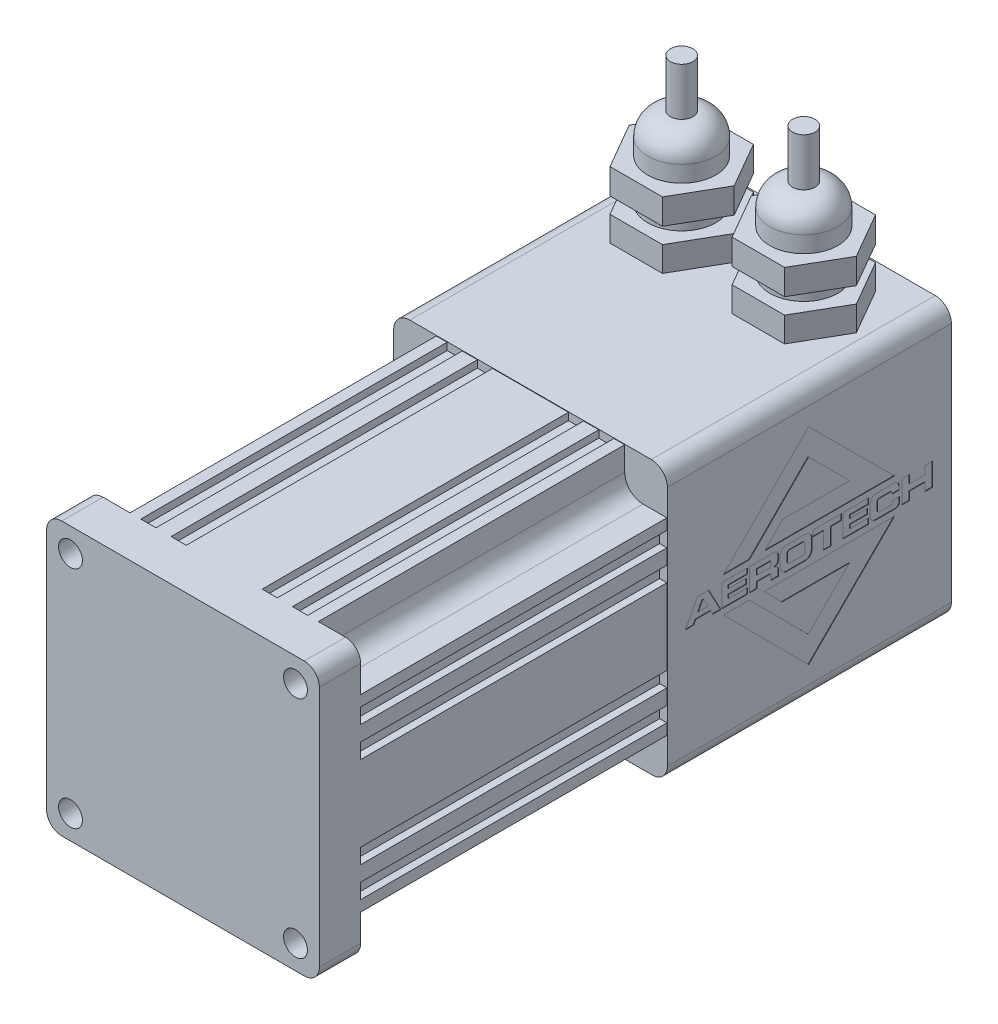
SolidWorks part; units mm, degrees
ref_plane "Front" through (0, 0, 0) normal (0, 0, 1) x (1, 0, 0)
ref_plane "Top" through (0, 0, 0) normal (0, 1, 0) x (1, 0, 0)
ref_plane "Right" through (0, 0, 0) normal (1, 0, 0) x (0, 0, -1)
sketch "Sketch1" plane through (0, 0, 0) normal (0, 0, 1) x (1, 0, 0)
  line L0 (-25.4, 28.575) -> (25.4, 28.575)
  line L1 (-28.575, -25.4) -> (-28.575, 25.4)
  line L2 (25.4, -28.575) -> (-25.4, -28.575)
  line L3 (28.575, 25.4) -> (28.575, -25.4)
  line L4 (-23.5712, -23.5712) -> (-23.5712, 23.5712) construction
  line L5 (-23.5712, 23.5712) -> (23.5712, 23.5712) construction
  line L6 (23.5712, 23.5712) -> (23.5712, -23.5712) construction
  line L7 (23.5712, -23.5712) -> (-23.5712, -23.5712) construction
  line L8 (0, -49.1414) -> (0, 49.1414) construction
  line L9 (31.5425, 0) -> (-31.5425, 0) construction
  arc A0 (28.575, 25.4) -> (25.4, 28.575) centre (25.4, 25.4) ccw
  arc A1 (-25.4, 28.575) -> (-28.575, 25.4) centre (-25.4, 25.4) ccw
  arc A2 (-28.575, -25.4) -> (-25.4, -28.575) centre (-25.4, -25.4) ccw
  arc A3 (25.4, -28.575) -> (28.575, -25.4) centre (25.4, -25.4) ccw
  circle A4 centre (-23.5712, -23.5712) radius 2.5
  circle A5 centre (23.5712, -23.5712) radius 2.5
  circle A6 centre (23.5712, 23.5712) radius 2.5
  circle A7 centre (-23.5712, 23.5712) radius 2.5
  point P20 (0, 28.575)
  point P23 (28.575, 0)
  point P26 (23.5712, 0)
  point P27 (-23.5712, 0)
  point P28 (0, 23.5712)
  dimension "D1" = 3.175
  dimension "D2" = 57.15
  dimension "D4" = 5
  dimension "D5" = 47.1424
  dimension "D3" = 57.15
  dimension "D6" = 47.1424
extrude "Front Mount Plate" add sketch "Sketch1" along normal blind 8.64
sketch "Sketch2" plane through (0, 0, 0) normal (0, 0, -1) x (-1, 0, 0)
  line L0 (-28.575, -25.4) -> (-28.575, 25.4) construction
  line L1 (25.4, -28.575) -> (-25.4, -28.575) construction
  line L2 (28.575, 25.4) -> (28.575, -25.4) construction
  line L3 (-25.4, 28.575) -> (25.4, 28.575) construction
  line L4 (-28.575, -25.4) -> (-28.575, 25.4)
  line L5 (25.4, -28.575) -> (-25.4, -28.575)
  line L6 (28.575, 25.4) -> (28.575, -25.4)
  line L7 (-25.4, 28.575) -> (25.4, 28.575)
  arc A0 (-28.575, -25.4) -> (-25.4, -28.575) centre (-25.4, -25.4) ccw construction
  arc A1 (25.4, -28.575) -> (28.575, -25.4) centre (25.4, -25.4) ccw construction
  arc A2 (28.575, 25.4) -> (25.4, 28.575) centre (25.4, 25.4) ccw construction
  arc A3 (-25.4, 28.575) -> (-28.575, 25.4) centre (-25.4, 25.4) ccw construction
  arc A4 (-28.575, -25.4) -> (-25.4, -28.575) centre (-25.4, -25.4) ccw
  arc A5 (25.4, -28.575) -> (28.575, -25.4) centre (25.4, -25.4) ccw
  arc A6 (28.575, 25.4) -> (25.4, 28.575) centre (25.4, 25.4) ccw
  arc A7 (-25.4, 28.575) -> (-28.575, 25.4) centre (-25.4, 25.4) ccw
extrude "Motor" add sketch "Sketch2" along normal blind 64.18
sketch "Sketch3" plane through (0, 0, 0) normal (0, 0, 1) x (1, 0, 0)
  line L0 (-28.575, 19.7358) -> (-23.5712, 19.7358)
  line L1 (-19.7358, 28.575) -> (-17.4752, 28.575)
  line L2 (-17.4752, 28.575) -> (-17.4752, 27.051)
  line L3 (-17.4752, 27.051) -> (-14.3002, 27.051)
  line L4 (-14.3002, 27.051) -> (-14.3002, 28.575)
  line L5 (-14.3002, 28.575) -> (-11.1252, 28.575)
  line L6 (-11.1252, 28.575) -> (-11.1252, 27.051)
  line L7 (-11.1252, 27.051) -> (-7.9502, 27.051)
  line L8 (-7.9502, 27.051) -> (-7.9502, 28.575)
  line L9 (-7.9502, 28.575) -> (7.9502, 28.575)
  line L10 (7.9502, 28.575) -> (7.9502, 27.051)
  line L11 (7.9502, 27.051) -> (11.1252, 27.051)
  line L12 (11.1252, 27.051) -> (11.1252, 28.575)
  line L13 (11.1252, 28.575) -> (14.3002, 28.575)
  line L14 (14.3002, 28.575) -> (14.3002, 27.051)
  line L15 (14.3002, 27.051) -> (17.4752, 27.051)
  line L16 (17.4752, 27.051) -> (17.4752, 28.575)
  line L17 (17.4752, 28.575) -> (19.7358, 28.575)
  line L18 (-19.7358, 28.575) -> (-19.7358, 23.5712)
  line L19 (-25.4, 28.575) -> (25.4, 28.575) construction
  line L20 (-28.575, -25.4) -> (-28.575, 25.4) construction
  line L21 (17.4752, 28.575) -> (14.3002, 28.575)
  line L22 (11.1252, 28.575) -> (7.9502, 28.575)
  line L23 (7.9502, 28.575) -> (8.0896, 28.5819)
  line L24 (-7.9502, 28.575) -> (-11.1252, 28.575)
  line L25 (-14.3002, 28.575) -> (-17.4752, 28.575)
  line L26 (-25.4, 28.575) -> (-19.7358, 28.575)
  line L27 (-28.575, 25.4) -> (-28.575, 19.7358)
  arc A0 (-23.5712, 19.7358) -> (-19.7358, 23.5712) centre (-23.5712, 23.5712) ccw
  arc A1 (-25.4, 28.575) -> (-28.575, 25.4) centre (-25.4, 25.4) ccw construction
  arc A2 (-25.4, 28.575) -> (-28.575, 25.4) centre (-25.4, 25.4) ccw
  dimension "D3" = 3.8354
  dimension "D1" = 3.175
  dimension "D2" = 1.524
  dimension "D4" = 8.8392
  dimension "D5" = 8.8392
  dimension "D6" = 15.9004
  dimension "D7" = 2.2606
extrude "Motor Fins" cut sketch "Sketch3" against normal through all contours L16 L21 L14 L15 | L12 L22 L10 L11 | L8 L24 L6 L7 | L4 L25 L2 L3 | L26 A2 L27 L0 A0 L18
ref_axis "Axis1" through (0, 0, -130.3065) along (0, 0, 1)
pattern_circular "Motor Fins Pattern" count 4 over 270 about axis through (0, 0, 0) along (0, 0, 1) of "Motor Fins"
sketch "Sketch4" plane through (0, 0, -64.18) normal (0, 0, -1) x (-1, 0, 0)
  line L0 (-25.3, 28.675) -> (25.3, 28.675)
  line L1 (28.675, 25.3) -> (28.675, -25.3)
  line L2 (25.5, -28.475) -> (-25.5, -28.475)
  line L3 (-28.675, -25.3) -> (-28.675, 25.3)
  line L4 (0, 28.675) -> (0, 0) construction
  line L5 (0, 0) -> (28.675, 0) construction
  line L6 (7.9502, 28.575) -> (-7.9502, 28.575) construction
  line L7 (-28.575, 7.9502) -> (-28.575, -7.9502) construction
  line L8 (-7.9502, -28.575) -> (7.9502, -28.575) construction
  line L10 (28.575, -7.9502) -> (28.575, 7.9502) construction
  arc A4 (-28.675, -25.3) -> (-25.5, -28.475) centre (-25.5, -25.3) ccw
  arc A5 (25.5, -28.475) -> (28.675, -25.3) centre (25.5, -25.3) ccw
  arc A6 (28.675, 25.3) -> (25.3, 28.675) centre (25.3, 25.3) ccw
  arc A7 (-25.3, 28.675) -> (-28.675, 25.3) centre (-25.3, 25.3) ccw
  arc A8 (-28.575, -25.4) -> (-25.4, -28.575) centre (-25.4, -25.4) ccw construction
  arc A9 (25.4, -28.575) -> (28.575, -25.4) centre (25.4, -25.4) ccw construction
  dimension "D1" = 0.1
  dimension "D2" = 0.1
  dimension "D3" = 0.1
  dimension "D4" = 0.1
extrude "Enc Can" add sketch "Sketch4" along normal blind 59.51
sketch "Sketch11" plane through (28.675, 0, 0) normal (1, 0, 0) x (0, 0, -1)
  line L0 (88.9565, 2.3168) -> (93.1221, 2.3168)
  line L1 (94.4835, 0.9554) -> (94.4835, -1.0386)
  line L2 (93.0789, -2.4432) -> (89.2687, -2.4432)
  line L3 (87.8027, -0.9773) -> (87.8027, 0.9554)
  line L4 (91.0794, 1.1637) -> (92.5563, 1.1637)
  line L5 (92.998, 0.722) -> (92.998, -0.8097)
  line L6 (92.5621, -1.2456) -> (89.8225, -1.2456)
  line L7 (89.3492, -0.7722) -> (89.3492, 0.7301)
  line L8 (89.7934, 1.1715) -> (91.0794, 1.1637)
  line L9 (82.9208, 1.1044) -> (85.6816, 1.1044)
  line L10 (85.9333, 0.8526) -> (85.9333, 0.248)
  line L11 (85.6723, -0.0131) -> (82.9208, -0.0131)
  line L12 (82.9208, -0.0131) -> (82.9208, 1.1044)
  line L13 (81.4158, 2.3168) -> (86.5203, 2.3168)
  line L14 (87.4271, 1.41) -> (87.4271, 0.4495)
  line L15 (87.4271, -2.4432) -> (85.923, -2.4432)
  line L16 (85.923, -2.4432) -> (85.923, -1.6109)
  line L17 (85.5149, -1.2029) -> (82.9083, -1.2029)
  line L18 (82.9083, -1.2029) -> (82.9083, -2.4432)
  line L19 (82.9083, -2.4432) -> (81.4158, -2.4432)
  line L20 (81.4158, -2.4432) -> (81.4158, 2.3168)
  line L21 (111.2718, 0.54) -> (112.7627, 0.54)
  line L22 (112.7627, 0.54) -> (112.7627, 1.2972)
  line L23 (111.7431, 2.3168) -> (107.9351, 2.3168)
  line L24 (106.6708, 1.0525) -> (106.6708, -1.2129)
  line L25 (107.9011, -2.4432) -> (111.9771, -2.4432)
  line L26 (112.8433, -1.577) -> (112.8433, -0.6783)
  line L27 (112.8433, -0.6783) -> (111.3281, -0.6783)
  line L28 (111.3281, -0.6783) -> (111.3281, -0.9515)
  line L29 (110.9108, -1.3689) -> (108.715, -1.3689)
  line L30 (108.1674, -0.8212) -> (108.1674, 0.5695)
  line L31 (108.6971, 1.0992) -> (110.8691, 1.0992)
  line L32 (111.2718, 0.6965) -> (111.2718, 0.54)
  line L33 (67.9134, -2.4432) -> (70.519, 2.3168)
  line L34 (70.519, 2.3168) -> (72.8346, 2.3168)
  line L35 (72.8346, 2.3168) -> (75.3883, -2.4432)
  line L36 (75.3883, -2.4432) -> (73.679, -2.4432)
  line L37 (73.679, -2.4432) -> (73.2611, -1.6252)
  line L38 (73.2611, -1.6252) -> (70.1097, -1.6252)
  line L39 (70.1097, -1.6252) -> (69.6824, -2.4432)
  line L40 (69.6824, -2.4432) -> (67.9134, -2.4432)
  line L41 (70.6406, -0.5321) -> (72.7163, -0.5321)
  line L42 (72.7163, -0.5321) -> (71.8147, 1.1708)
  line L43 (71.8147, 1.1708) -> (71.5421, 1.1708)
  line L44 (71.5421, 1.1708) -> (70.6406, -0.5321)
  line L45 (75.5917, 2.3168) -> (80.9222, 2.3168)
  line L46 (80.9222, 2.3168) -> (80.9222, 1.178)
  line L47 (80.9222, 1.178) -> (77.0104, 1.178)
  line L48 (77.0104, 1.178) -> (77.0104, 0.5173)
  line L49 (77.0104, 0.5173) -> (80.7195, 0.5173)
  line L50 (80.7195, 0.5173) -> (80.7195, -0.5529)
  line L51 (80.7195, -0.5529) -> (77.0104, -0.5529)
  line L52 (77.0104, -0.5529) -> (77.0104, -1.2947)
  line L53 (77.0104, -1.2947) -> (80.9222, -1.2947)
  line L54 (80.9222, -1.2947) -> (80.9222, -2.4432)
  line L55 (80.9222, -2.4432) -> (75.5917, -2.4432)
  line L56 (75.5917, -2.4432) -> (75.5917, 2.3168)
  line L57 (94.7459, 2.3168) -> (100.6554, 2.3168)
  line L58 (100.6554, 2.3168) -> (100.6554, 1.0852)
  line L59 (100.6554, 1.0852) -> (98.455, 1.0852)
  line L60 (98.455, 1.0852) -> (98.455, -2.4432)
  line L61 (98.455, -2.4432) -> (96.8755, -2.4432)
  line L62 (96.8755, -2.4432) -> (96.8755, 1.0844)
  line L63 (96.8755, 1.0844) -> (94.7459, 1.0844)
  line L64 (94.7459, 1.0844) -> (94.7459, 2.3168)
  line L65 (100.9451, 2.3168) -> (106.3069, 2.3168)
  line L66 (106.3069, 2.3168) -> (106.3069, 1.177)
  line L67 (106.3069, 1.177) -> (102.4198, 1.177)
  line L68 (102.4198, 1.177) -> (102.4198, 0.5302)
  line L69 (102.4198, 0.5302) -> (106.1167, 0.5302)
  line L70 (106.1167, 0.5302) -> (106.1167, -0.5415)
  line L71 (106.1167, -0.5415) -> (102.4198, -0.5415)
  line L72 (102.4198, -0.5415) -> (102.4198, -1.2892)
  line L73 (102.4198, -1.2892) -> (106.3069, -1.2892)
  line L74 (106.3069, -1.2892) -> (106.3069, -2.4432)
  line L75 (106.3069, -2.4432) -> (100.9451, -2.4432)
  line L76 (100.9451, -2.4432) -> (100.9451, 2.3168)
  line L77 (113.3445, 2.3168) -> (114.895, 2.3168)
  line L78 (114.895, 2.3168) -> (114.895, 0.6117)
  line L79 (114.895, 0.6117) -> (118.1704, 0.6117)
  line L80 (118.1704, 0.6117) -> (118.1704, 2.3168)
  line L81 (118.1704, 2.3168) -> (119.7597, 2.3168)
  line L82 (119.7597, 2.3168) -> (119.7597, -2.4432)
  line L83 (119.7597, -2.4432) -> (118.1704, -2.4432)
  line L84 (118.1704, -2.4432) -> (118.1704, -0.7247)
  line L85 (118.1704, -0.7247) -> (114.895, -0.7247)
  line L86 (114.895, -0.7247) -> (114.895, -2.4432)
  line L87 (114.895, -2.4432) -> (113.3445, -2.4432)
  line L88 (113.3445, -2.4432) -> (113.3445, 2.3168)
  line L89 (75.9285, -3.7308) -> (81.3786, -3.7308)
  line L90 (81.3786, -3.7308) -> (93.6773, -16.0962)
  line L91 (93.6773, -16.0962) -> (102.3262, -7.494)
  line L92 (102.3262, -7.494) -> (88.1992, -7.494)
  line L93 (88.1992, -7.494) -> (84.4729, -3.7308)
  line L94 (84.4729, -3.7308) -> (111.7772, -3.7308)
  line L95 (111.7772, -3.7308) -> (93.7559, -21.6549)
  line L96 (93.7559, -21.6549) -> (75.9285, -3.7308)
  line L97 (75.9285, 3.6038) -> (93.7559, 21.5279)
  line L98 (93.7559, 21.5279) -> (111.7772, 3.6038)
  line L99 (75.9285, 3.6038) -> (81.3786, 3.6038)
  line L100 (81.3786, 3.6038) -> (93.7413, 16.0335)
  line L101 (93.7413, 16.0335) -> (102.3901, 7.4313)
  line L102 (102.3901, 7.4313) -> (88.2631, 7.4313)
  line L103 (88.2631, 7.4313) -> (84.6029, 3.6038)
  line L104 (84.6029, 3.6038) -> (111.7772, 3.6038)
  line L105 (87.4271, -1.2037) -> (87.4271, -2.4432)
  line L106 (-23.1846, 0) -> (123.69, 0) construction
  line L107 (93.935, 25.3) -> (93.935, -74.4783) construction
  line L108 (123.69, 25.3) -> (64.18, 25.3) construction
  line L109 (123.69, 25.3) -> (123.69, -25.3) construction
  arc A0 (93.1221, 2.3168) -> (94.4835, 0.9554) centre (93.1221, 0.9554) cw
  arc A1 (94.4835, -1.0386) -> (93.0789, -2.4432) centre (93.0789, -1.0386) cw
  arc A2 (89.2687, -2.4432) -> (87.8027, -0.9773) centre (89.2687, -0.9773) cw
  arc A3 (87.8027, 0.9554) -> (88.9565, 2.3168) centre (89.1828, 0.9554) cw
  arc A4 (92.5563, 1.1637) -> (92.998, 0.722) centre (92.5563, 0.722) cw
  arc A5 (92.998, -0.8097) -> (92.5621, -1.2456) centre (92.5621, -0.8097) cw
  arc A6 (89.8225, -1.2456) -> (89.3492, -0.7722) centre (89.8225, -0.7722) cw
  arc A7 (89.3492, 0.7301) -> (89.7934, 1.1715) centre (89.7907, 0.7301) cw
  arc A8 (85.6816, 1.1044) -> (85.9333, 0.8526) centre (85.6816, 0.8526) cw
  arc A9 (85.9333, 0.248) -> (85.6723, -0.0131) centre (85.6723, 0.248) cw
  arc A10 (85.923, -1.6109) -> (85.5149, -1.2029) centre (85.5149, -1.6109) ccw
  arc A11 (87.4271, 1.41) -> (86.5203, 2.3168) centre (86.5203, 1.41) ccw
  arc A12 (87.4271, 0.4495) -> (86.611, -0.3666) centre (86.611, 0.4495) cw
  arc A13 (86.611, -0.3666) -> (87.4271, -1.2037) centre (86.611, -1.1829) cw
  arc A14 (112.7627, 1.2972) -> (111.7431, 2.3168) centre (111.7431, 1.2972) ccw
  arc A15 (107.9351, 2.3168) -> (106.6708, 1.0525) centre (107.9351, 1.0525) ccw
  arc A16 (106.6708, -1.2129) -> (107.9011, -2.4432) centre (107.9011, -1.2129) ccw
  arc A17 (111.9771, -2.4432) -> (112.8433, -1.577) centre (111.9771, -1.577) ccw
  arc A18 (111.3281, -0.9515) -> (110.9108, -1.3689) centre (110.9108, -0.9515) cw
  arc A19 (108.715, -1.3689) -> (108.1674, -0.8212) centre (108.715, -0.8212) cw
  arc A20 (108.1674, 0.5695) -> (108.6971, 1.0992) centre (108.6971, 0.5695) cw
  arc A21 (110.8691, 1.0992) -> (111.2718, 0.6965) centre (110.8691, 0.6965) cw
extrude "Logo-1" cut sketch "Sketch11" against normal blind 0.1
sketch "Sketch12" plane through (-28.675, 0, 0) normal (-1, 0, 0) x (0, 0, 1)
  line L0 (-98.7553, 2.3168) -> (-94.5897, 2.3168)
  line L1 (-93.2283, 0.9554) -> (-93.2283, -1.0386)
  line L2 (-94.6329, -2.4432) -> (-98.4432, -2.4432)
  line L3 (-99.9091, -0.9773) -> (-99.9091, 0.9554)
  line L4 (-96.6324, 1.1637) -> (-95.1555, 1.1637)
  line L5 (-94.7138, 0.722) -> (-94.7138, -0.8097)
  line L6 (-95.1498, -1.2456) -> (-97.8893, -1.2456)
  line L7 (-98.3627, -0.7722) -> (-98.3627, 0.7301)
  line L8 (-97.9185, 1.1715) -> (-96.6324, 1.1637)
  line L9 (-104.791, 1.1044) -> (-102.0303, 1.1044)
  line L10 (-101.7785, 0.8526) -> (-101.7785, 0.248)
  line L11 (-102.0396, -0.0131) -> (-104.791, -0.0131)
  line L12 (-104.791, -0.0131) -> (-104.791, 1.1044)
  line L13 (-106.2961, 2.3168) -> (-101.1915, 2.3168)
  line L14 (-100.2847, 1.41) -> (-100.2847, 0.4495)
  line L15 (-100.2847, -2.4432) -> (-101.7889, -2.4432)
  line L16 (-101.7889, -2.4432) -> (-101.7889, -1.6109)
  line L17 (-102.1969, -1.2029) -> (-104.8035, -1.2029)
  line L18 (-104.8035, -1.2029) -> (-104.8035, -2.4432)
  line L19 (-104.8035, -2.4432) -> (-106.2961, -2.4432)
  line L20 (-106.2961, -2.4432) -> (-106.2961, 2.3168)
  line L21 (-76.4401, 0.54) -> (-74.9491, 0.54)
  line L22 (-74.9491, 0.54) -> (-74.9491, 1.2972)
  line L23 (-75.9688, 2.3168) -> (-79.7768, 2.3168)
  line L24 (-81.041, 1.0525) -> (-81.041, -1.2129)
  line L25 (-79.8107, -2.4432) -> (-75.7348, -2.4432)
  line L26 (-74.8685, -1.577) -> (-74.8685, -0.6783)
  line L27 (-74.8685, -0.6783) -> (-76.3838, -0.6783)
  line L28 (-76.3838, -0.6783) -> (-76.3838, -0.9515)
  line L29 (-76.8011, -1.3689) -> (-78.9968, -1.3689)
  line L30 (-79.5444, -0.8212) -> (-79.5444, 0.5695)
  line L31 (-79.0147, 1.0992) -> (-76.8428, 1.0992)
  line L32 (-76.4401, 0.6965) -> (-76.4401, 0.54)
  line L33 (-119.7984, -2.4432) -> (-117.1928, 2.3168)
  line L34 (-117.1928, 2.3168) -> (-114.8773, 2.3168)
  line L35 (-114.8773, 2.3168) -> (-112.3236, -2.4432)
  line L36 (-112.3236, -2.4432) -> (-114.0328, -2.4432)
  line L37 (-114.0328, -2.4432) -> (-114.4507, -1.6252)
  line L38 (-114.4507, -1.6252) -> (-117.6021, -1.6252)
  line L39 (-117.6021, -1.6252) -> (-118.0294, -2.4432)
  line L40 (-118.0294, -2.4432) -> (-119.7984, -2.4432)
  line L41 (-117.0713, -0.5321) -> (-114.9956, -0.5321)
  line L42 (-114.9956, -0.5321) -> (-115.8971, 1.1708)
  line L43 (-115.8971, 1.1708) -> (-116.1698, 1.1708)
  line L44 (-116.1698, 1.1708) -> (-117.0713, -0.5321)
  line L45 (-112.1202, 2.3168) -> (-106.7896, 2.3168)
  line L46 (-106.7896, 2.3168) -> (-106.7896, 1.178)
  line L47 (-106.7896, 1.178) -> (-110.7014, 1.178)
  line L48 (-110.7014, 1.178) -> (-110.7014, 0.5173)
  line L49 (-110.7014, 0.5173) -> (-106.9923, 0.5173)
  line L50 (-106.9923, 0.5173) -> (-106.9923, -0.5529)
  line L51 (-106.9923, -0.5529) -> (-110.7014, -0.5529)
  line L52 (-110.7014, -0.5529) -> (-110.7014, -1.2947)
  line L53 (-110.7014, -1.2947) -> (-106.7896, -1.2947)
  line L54 (-106.7896, -1.2947) -> (-106.7896, -2.4432)
  line L55 (-106.7896, -2.4432) -> (-112.1202, -2.4432)
  line L56 (-112.1202, -2.4432) -> (-112.1202, 2.3168)
  line L57 (-92.9659, 2.3168) -> (-87.0565, 2.3168)
  line L58 (-87.0565, 2.3168) -> (-87.0565, 1.0852)
  line L59 (-87.0565, 1.0852) -> (-89.2568, 1.0852)
  line L60 (-89.2568, 1.0852) -> (-89.2568, -2.4432)
  line L61 (-89.2568, -2.4432) -> (-90.8363, -2.4432)
  line L62 (-90.8363, -2.4432) -> (-90.8363, 1.0844)
  line L63 (-90.8363, 1.0844) -> (-92.9659, 1.0844)
  line L64 (-92.9659, 1.0844) -> (-92.9659, 2.3168)
  line L65 (-86.7668, 2.3168) -> (-81.4049, 2.3168)
  line L66 (-81.4049, 2.3168) -> (-81.4049, 1.177)
  line L67 (-81.4049, 1.177) -> (-85.2921, 1.177)
  line L68 (-85.2921, 1.177) -> (-85.2921, 0.5302)
  line L69 (-85.2921, 0.5302) -> (-81.5952, 0.5302)
  line L70 (-81.5952, 0.5302) -> (-81.5952, -0.5415)
  line L71 (-81.5952, -0.5415) -> (-85.2921, -0.5415)
  line L72 (-85.2921, -0.5415) -> (-85.2921, -1.2892)
  line L73 (-85.2921, -1.2892) -> (-81.4049, -1.2892)
  line L74 (-81.4049, -1.2892) -> (-81.4049, -2.4432)
  line L75 (-81.4049, -2.4432) -> (-86.7668, -2.4432)
  line L76 (-86.7668, -2.4432) -> (-86.7668, 2.3168)
  line L77 (-74.3673, 2.3168) -> (-72.8168, 2.3168)
  line L78 (-72.8168, 2.3168) -> (-72.8168, 0.6117)
  line L79 (-72.8168, 0.6117) -> (-69.5414, 0.6117)
  line L80 (-69.5414, 0.6117) -> (-69.5414, 2.3168)
  line L81 (-69.5414, 2.3168) -> (-67.9521, 2.3168)
  line L82 (-67.9521, 2.3168) -> (-67.9521, -2.4432)
  line L83 (-67.9521, -2.4432) -> (-69.5414, -2.4432)
  line L84 (-69.5414, -2.4432) -> (-69.5414, -0.7247)
  line L85 (-69.5414, -0.7247) -> (-72.8168, -0.7247)
  line L86 (-72.8168, -0.7247) -> (-72.8168, -2.4432)
  line L87 (-72.8168, -2.4432) -> (-74.3673, -2.4432)
  line L88 (-74.3673, -2.4432) -> (-74.3673, 2.3168)
  line L89 (-111.7834, -3.7308) -> (-106.3332, -3.7308)
  line L90 (-106.3332, -3.7308) -> (-94.0345, -16.0962)
  line L91 (-94.0345, -16.0962) -> (-85.3857, -7.494)
  line L92 (-85.3857, -7.494) -> (-99.5127, -7.494)
  line L93 (-99.5127, -7.494) -> (-103.239, -3.7308)
  line L94 (-103.239, -3.7308) -> (-75.9346, -3.7308)
  line L95 (-75.9346, -3.7308) -> (-93.9559, -21.6549)
  line L96 (-93.9559, -21.6549) -> (-111.7834, -3.7308)
  line L97 (-111.7834, 3.6038) -> (-93.9559, 21.5279)
  line L98 (-93.9559, 21.5279) -> (-75.9346, 3.6038)
  line L99 (-111.7834, 3.6038) -> (-106.3332, 3.6038)
  line L100 (-106.3332, 3.6038) -> (-93.9706, 16.0335)
  line L101 (-93.9706, 16.0335) -> (-85.3217, 7.4313)
  line L102 (-85.3217, 7.4313) -> (-99.4488, 7.4313)
  line L103 (-99.4488, 7.4313) -> (-103.109, 3.6038)
  line L104 (-103.109, 3.6038) -> (-75.9346, 3.6038)
  line L105 (-100.2847, -1.2037) -> (-100.2847, -2.4432)
  line L106 (-123.69, 0) -> (-14.3476, 0) construction
  line L107 (-93.935, 51.8999) -> (-93.935, -28.475) construction
  line L108 (-123.69, -25.3) -> (-123.69, 25.3) construction
  line L109 (-123.69, -28.475) -> (-64.18, -28.475) construction
  arc A0 (-94.5897, 2.3168) -> (-93.2283, 0.9554) centre (-94.5897, 0.9554) cw
  arc A1 (-93.2283, -1.0386) -> (-94.6329, -2.4432) centre (-94.6329, -1.0386) cw
  arc A2 (-98.4432, -2.4432) -> (-99.9091, -0.9773) centre (-98.4432, -0.9773) cw
  arc A3 (-99.9091, 0.9554) -> (-98.7553, 2.3168) centre (-98.529, 0.9554) cw
  arc A4 (-95.1555, 1.1637) -> (-94.7138, 0.722) centre (-95.1555, 0.722) cw
  arc A5 (-94.7138, -0.8097) -> (-95.1498, -1.2456) centre (-95.1498, -0.8097) cw
  arc A6 (-97.8893, -1.2456) -> (-98.3627, -0.7722) centre (-97.8893, -0.7722) cw
  arc A7 (-98.3627, 0.7301) -> (-97.9185, 1.1715) centre (-97.9212, 0.7301) cw
  arc A8 (-102.0303, 1.1044) -> (-101.7785, 0.8526) centre (-102.0303, 0.8526) cw
  arc A9 (-101.7785, 0.248) -> (-102.0396, -0.0131) centre (-102.0396, 0.248) cw
  arc A10 (-101.7889, -1.6109) -> (-102.1969, -1.2029) centre (-102.1969, -1.6109) ccw
  arc A11 (-100.2847, 1.41) -> (-101.1915, 2.3168) centre (-101.1915, 1.41) ccw
  arc A12 (-100.2847, 0.4495) -> (-101.1008, -0.3666) centre (-101.1008, 0.4495) cw
  arc A13 (-101.1008, -0.3666) -> (-100.2847, -1.2037) centre (-101.1008, -1.1829) cw
  arc A14 (-74.9491, 1.2972) -> (-75.9688, 2.3168) centre (-75.9688, 1.2972) ccw
  arc A15 (-79.7768, 2.3168) -> (-81.041, 1.0525) centre (-79.7768, 1.0525) ccw
  arc A16 (-81.041, -1.2129) -> (-79.8107, -2.4432) centre (-79.8107, -1.2129) ccw
  arc A17 (-75.7348, -2.4432) -> (-74.8685, -1.577) centre (-75.7348, -1.577) ccw
  arc A18 (-76.3838, -0.9515) -> (-76.8011, -1.3689) centre (-76.8011, -0.9515) cw
  arc A19 (-78.9968, -1.3689) -> (-79.5444, -0.8212) centre (-78.9968, -0.8212) cw
  arc A20 (-79.5444, 0.5695) -> (-79.0147, 1.0992) centre (-79.0147, 0.5695) cw
  arc A21 (-76.8428, 1.0992) -> (-76.4401, 0.6965) centre (-76.8428, 0.6965) cw
extrude "Logo-2" cut sketch "Sketch12" against normal blind 0.1
ref_plane "Plane1" through (0, 0, -108.65) normal (0, 0, -1) x (-1, 0, 0)
sketch "Sketch5" plane through (0, 0, -108.65) normal (0, 0, 1) x (1, 0, 0)
  line L0 (-19.9197, 45.9978) -> (-19.9197, 28.675)
  line L1 (-12.795, 22.8926) -> (-12.795, 66.8878) construction
  line L2 (-15.1445, 50.773) -> (-15.1445, 60.773)
  line L3 (-15.1445, 60.773) -> (-12.795, 60.773)
  line L4 (-28.675, -25.3) -> (-28.675, 25.3) construction
  line L5 (-25.3, 28.675) -> (25.3, 28.675) construction
  line L6 (-19.9197, 28.675) -> (-12.795, 28.675)
  line L7 (-12.795, 28.675) -> (-12.795, 60.773)
  arc A1 (-15.1445, 50.773) -> (-19.9197, 45.9978) centre (-15.1445, 45.9978) ccw
  dimension "D1" = 4.7752
  dimension "D2" = 17.3228
  dimension "D3" = 32.098
  dimension "D4" = 2.3495
  dimension "D5" = 22.098
  dimension "D6" = 15.88
revolve "Revolve1" add sketch "Sketch5" angle 360 about L1
sketch "Sketch6" plane through (0, 28.575, 0) normal (0, 1, 0) x (-1, 0, 0)
  line L0 (1.795, -108.65) -> (23.795, -108.65) construction
  line L1 (7.295, -118.1763) -> (18.295, -118.1763)
  line L2 (18.295, -118.1763) -> (23.795, -108.65)
  line L3 (23.795, -108.65) -> (18.295, -99.1237)
  line L4 (18.295, -99.1237) -> (7.295, -99.1237)
  line L5 (7.295, -99.1237) -> (1.795, -108.65)
  line L6 (1.795, -108.65) -> (7.295, -118.1763)
  circle A0 centre (12.795, -108.65) radius 7.1247 construction
  circle A1 centre (12.795, -108.65) radius 7.1247
  point P10 (12.795, -108.65)
  dimension "D1" = 11
extrude "Extrude4" add sketch "Sketch6" along normal blind 5.33
ref_plane "Plane2" through (0, 35.57, 0) normal (0, 1, 0) x (-1, 0, 0)
mirror "Mirror2" about plane through (0, 35.57, 0) normal (0, 1, 0) of "Extrude4"
mirror "Mirror3" about plane through (0, 0, 0) normal (1, 0, 0) of "Revolve1", "Mirror2", "Extrude4"
sketch "Sketch13" plane through (0, 0, 8.64) normal (0, 0, 1) x (1, 0, 0)
  line L0 (-25.4, -28.575) -> (25.4, -28.575) construction
  line L1 (28.575, -25.4) -> (28.575, 25.4) construction
  line L2 (25.4, 28.575) -> (-25.4, 28.575) construction
  line L3 (-28.575, 25.4) -> (-28.575, -25.4) construction
  line L4 (-25.4, -28.575) -> (25.4, -28.575)
  line L5 (28.575, -25.4) -> (28.575, 25.4)
  line L6 (25.4, 28.575) -> (-25.4, 28.575)
  line L7 (-28.575, 25.4) -> (-28.575, -25.4)
  arc A0 (-28.575, -25.4) -> (-25.4, -28.575) centre (-25.4, -25.4) ccw construction
  arc A1 (25.4, -28.575) -> (28.575, -25.4) centre (25.4, -25.4) ccw construction
  arc A2 (28.575, 25.4) -> (25.4, 28.575) centre (25.4, 25.4) ccw construction
  arc A3 (-25.4, 28.575) -> (-28.575, 25.4) centre (-25.4, 25.4) ccw construction
  arc A4 (-28.575, -25.4) -> (-25.4, -28.575) centre (-25.4, -25.4) ccw
  arc A5 (25.4, -28.575) -> (28.575, -25.4) centre (25.4, -25.4) ccw
  arc A6 (28.575, 25.4) -> (25.4, 28.575) centre (25.4, 25.4) ccw
  arc A7 (-25.4, 28.575) -> (-28.575, 25.4) centre (-25.4, 25.4) ccw
  circle A8 centre (-23.5712, -23.5712) radius 2.5 construction
  circle A9 centre (23.5712, -23.5712) radius 2.5 construction
  circle A10 centre (23.5712, 23.5712) radius 2.5 construction
  circle A11 centre (-23.5712, 23.5712) radius 2.5 construction
  circle A12 centre (-23.5712, -23.5712) radius 2.5
  circle A13 centre (23.5712, -23.5712) radius 2.5
  circle A14 centre (23.5712, 23.5712) radius 2.5
  circle A15 centre (-23.5712, 23.5712) radius 2.5
extrude "BRK Can" [suppressed] add sketch "Sketch13" along normal blind 38.1
